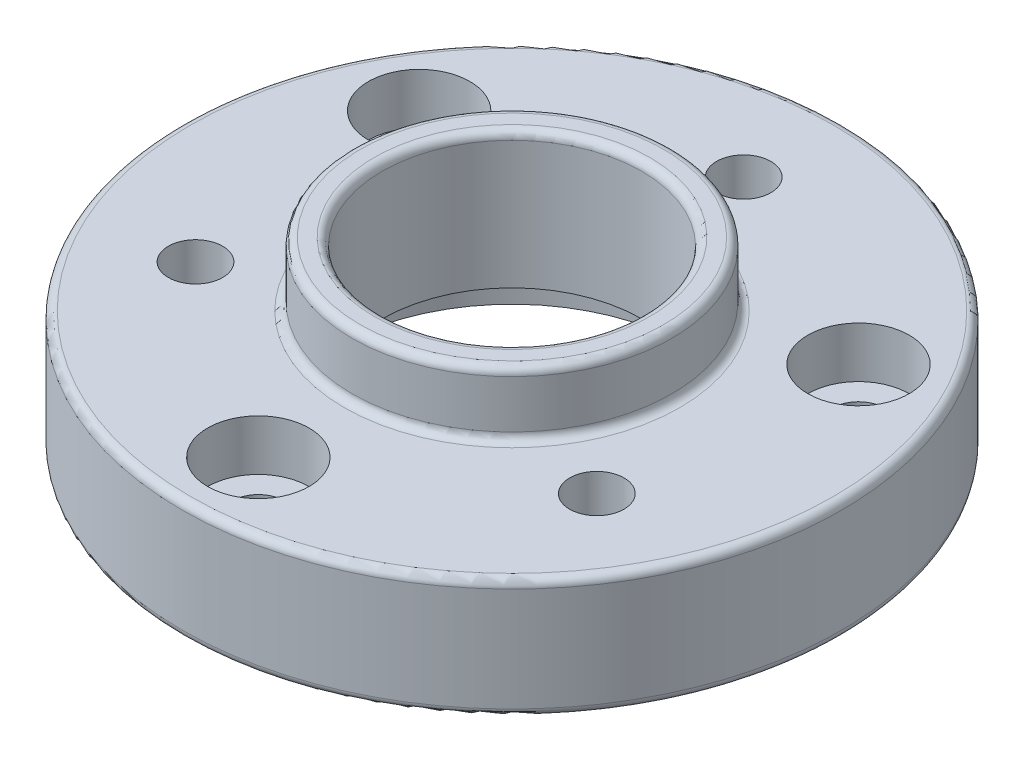
SolidWorks part; units mm, degrees
material "6061 Alloy"
ref_plane "Front Plane" through (0, 0, 0) normal (0, 0, 1) x (1, 0, 0)
ref_plane "Top Plane" through (0, 0, 0) normal (0, 1, 0) x (1, 0, 0)
ref_plane "Right Plane" through (0, 0, 0) normal (1, 0, 0) x (0, 0, -1)
sketch "Sketch2" plane through (0, 0, 0) normal (0, 1, 0) x (1, 0, 0)
  circle A0 centre (0, 0) radius 41.25
  dimension "D1" = 82.5
extrude "Boss-Extrude1" add sketch "Sketch2" along normal blind 15
sketch "Sketch3" plane through (0, 15, 0) normal (0, 1, 0) x (1, 0, 0)
  circle A0 centre (0, 0) radius 16.25
  circle A1 centre (0, 0) radius 20
  dimension "D1" = 40
  dimension "D2" = 32.5
extrude "Boss-Extrude2" add sketch "Sketch3" along normal blind 8
sketch "Sketch4" plane through (0, 15, 0) normal (0, 1, 0) x (1, 0, 0)
  circle A0 centre (0, 0) radius 16.25 construction
  circle A1 centre (0, 0) radius 16.25
extrude "Cut-Extrude1" cut sketch "Sketch4" against normal through all
sketch "Sketch5" plane through (0, 0, 0) normal (0, -1, 0) x (1, 0, 0)
  circle A0 centre (0, 0) radius 22.225
  circle A1 centre (0, 0) radius 16.25 construction
  circle A2 centre (0, 0) radius 16.25
  dimension "D1" = 44.45
extrude "Cut-Extrude2" cut sketch "Sketch5" against normal blind 6
sketch "Sketch8" plane through (0, 15, 0) normal (0, 1, 0) x (1, 0, 0)
  circle A0 centre (0, 0) radius 31.75 construction
  circle A1 centre (0, -31.75) radius 1.5109
  point P3 (0, -31.75)
  point P13 (-27.4963, 15.875)
  point P14 (27.4963, 15.875)
  dimension "D1" = 63.5
  dimension "D2" = 3
hole_wizard "CBORE for 1/4 Binding Head Machine Screw1" positions "Sketch8" profile "Sketch9" counterbore size "1/4" standard "ANSI Inch" end condition through all
sketch "Sketch9" plane through (27.4963, 15, -15.875) normal (1, 0, 0) x (0, 0, 1)
  line L0 (0, 0) -> (0, 15)
  line L1 (0, 15) -> (3.2639, 15)
  line L3 (3.2639, 15) -> (3.2639, 6.35)
  line L4 (3.2639, 6.35) -> (6.35, 6.35)
  line L5 (6.35, 6.35) -> (6.35, 0)
  line L7 (6.35, 0) -> (0, 0)
  line L11 (0, -6.35) -> (0, 107.95) construction
  dimension "Thru Hole Dia." = 6.5278
  dimension "Thru Hole Depth" = 15
  dimension "C'Bore Dia." = 12.7
  dimension "C'Bore Depth" = 6.35
fillet "Fillet1" radius 1 6 edges at (0, 6, -22.225) (0, 15, 20) (0, 23, 16.25) (0, 23, 20) (0, 0, 41.25) (0, 15, 41.25)
sketch "Sketch17" plane through (0, 15, 0) normal (0, 1, 0) x (1, 0, 0)
  circle A0 centre (0, 0) radius 29 construction
  dimension "D1" = 58
hole_wizard "M8x1.25 Tapped Hole1" positions "Sketch20" profile "Sketch19" tap size "M8x1.25" standard "ANSI Metric" end condition through all
sketch "Sketch20" plane through (0, 15, 0) normal (0, 1, 0) x (1, 0, 0)
  circle A0 centre (0, 0) radius 29 construction
  point P0 (0, 29)
  point P8 (25.1147, -14.5)
  point P9 (-25.1147, -14.5)
  dimension "D1" = 3
sketch "Sketch19" plane through (0, 15, -29) normal (1, 0, 0) x (0, 0, 1)
  line L0 (0, 0) -> (0, 15)
  line L1 (0, 15) -> (3.4, 15)
  line L2 (3.4, 15) -> (3.4, 0)
  line L5 (3.4, 0) -> (0, 0)
  line L11 (0, -6.35) -> (0, 107.95) construction
  dimension "Thru Tap Drill Dia." = 6.8
  dimension "Thru Tap Drill Depth" = 15
cosmetic thread "Hole Thread1"
cosmetic thread "Hole Thread2"
cosmetic thread "Hole Thread3"
equation "\"OD\"=82.5"
equation "\"D1@Sketch2\"=\"OD\""
equation "\"Height\"= 15"
equation "\"D1@Boss-Extrude1\"=\"Height\""
equation "\"ID\"=32.5"
equation "\"D2@Sketch3\"=\"ID\""
equation "\"Male height\"= 8"
equation "\"D1@Boss-Extrude2\"=\"Male height\""
equation "\"Female ID\"= 44.45'Based off sholder width"
equation "\"D1@Sketch5\"=\"Female ID\""
equation "\"Female depth\"= 6"
equation "\"D1@Cut-Extrude2\"=\"Female depth\""
equation "\"OD part\"= 50"
